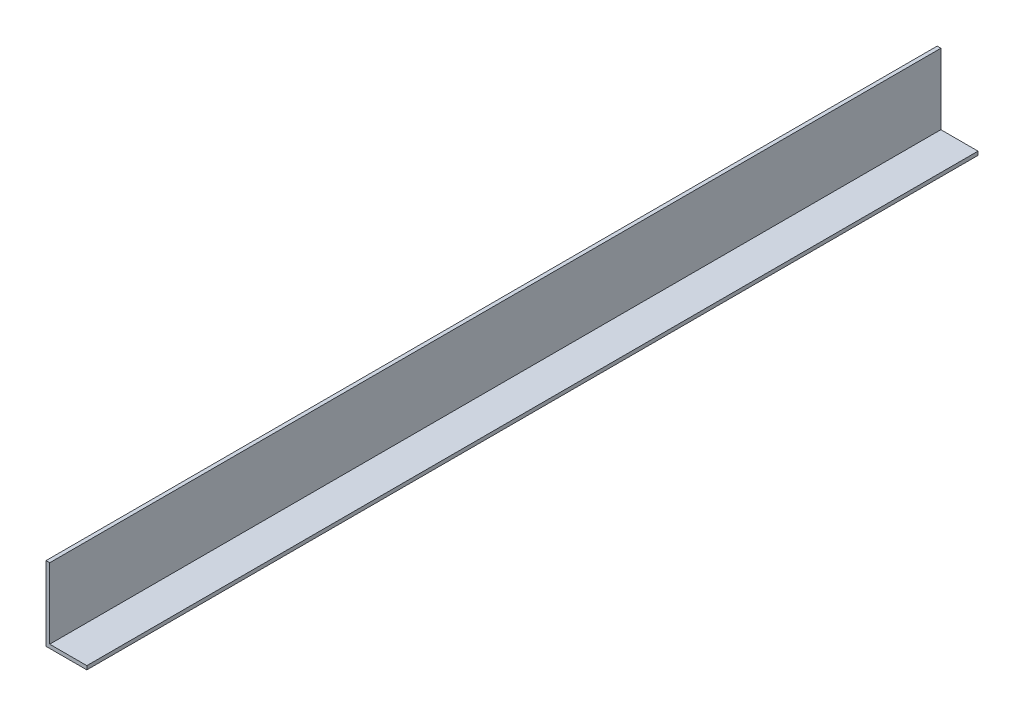
SolidWorks part; units mm, degrees
ref_plane "Plan de face" through (0, 0, 0) normal (0, 0, 1) x (1, 0, 0)
ref_plane "Plan de dessus" through (0, 0, 0) normal (0, 1, 0) x (1, 0, 0)
ref_plane "Plan de droite" through (0, 0, 0) normal (1, 0, 0) x (0, 0, -1)
sketch "Esquisse1" plane through (0, 0, 0) normal (0, 0, 1) x (1, 0, 0)
  line L0 (0, 0) -> (0, 20)
  line L1 (0, 20) -> (1, 20)
  line L2 (1, 20) -> (1, 1)
  line L3 (1, 1) -> (11, 1)
  line L4 (11, 1) -> (11, 0)
  line L5 (11, 0) -> (0, 0)
  dimension "D1" = 11
  dimension "D2" = 20
  dimension "D3" = 1
  dimension "D4" = 1
extrude "Boss.-Extru.1" add sketch "Esquisse1" along normal blind 240
sketch "Esquisse2" plane through (0, 0, 0) normal (-1, 0, 0) x (0, 0, 1)
  line L0 (120, 20) -> (120, 0) construction
  line L1 (240, 20) -> (0, 20) construction
  line L2 (240, 0) -> (0, 0) construction
  line L3 (120, 20) -> (115, 15)
  line L4 (115, 15) -> (110, 20)
  line L6 (110, 20) -> (105, 15)
  line L7 (105, 15) -> (100, 20)
  line L8 (100, 20) -> (95, 15)
  line L9 (95, 15) -> (90, 20)
  line L10 (90, 20) -> (85, 15)
  line L11 (85, 15) -> (80, 20)
  line L12 (80, 20) -> (75, 15)
  line L13 (75, 15) -> (70, 20)
  line L14 (70, 20) -> (65, 15)
  line L15 (65, 15) -> (60, 20)
  line L16 (60, 20) -> (55, 15)
  line L17 (55, 15) -> (50, 20)
  line L18 (50, 20) -> (45, 15)
  line L19 (45, 15) -> (40, 20)
  line L20 (40, 20) -> (35, 15)
  line L21 (35, 15) -> (30, 20)
  line L22 (30, 20) -> (25, 15)
  line L23 (25, 15) -> (20, 20)
  line L24 (20, 20) -> (15, 15)
  line L25 (15, 15) -> (10, 20)
  line L26 (10, 20) -> (5, 15)
  line L27 (5, 15) -> (0, 20)
  line L28 (235, 15) -> (240, 20)
  line L29 (230, 20) -> (235, 15)
  line L30 (225, 15) -> (230, 20)
  line L31 (220, 20) -> (225, 15)
  line L32 (215, 15) -> (220, 20)
  line L33 (210, 20) -> (215, 15)
  line L34 (205, 15) -> (210, 20)
  line L35 (200, 20) -> (205, 15)
  line L36 (195, 15) -> (200, 20)
  line L37 (190, 20) -> (195, 15)
  line L38 (185, 15) -> (190, 20)
  line L39 (180, 20) -> (185, 15)
  line L40 (175, 15) -> (180, 20)
  line L41 (170, 20) -> (175, 15)
  line L42 (165, 15) -> (170, 20)
  line L43 (160, 20) -> (165, 15)
  line L44 (155, 15) -> (160, 20)
  line L45 (150, 20) -> (155, 15)
  line L46 (145, 15) -> (150, 20)
  line L47 (140, 20) -> (145, 15)
  line L48 (135, 15) -> (140, 20)
  line L49 (130, 20) -> (135, 15)
  line L50 (125, 15) -> (130, 20)
  line L51 (120, 20) -> (125, 15)
  line L52 (0, 20) -> (0, 30)
  line L53 (0, 30) -> (240, 30)
  line L54 (240, 30) -> (240, 20)
  dimension "D1" = 10
  dimension "D3" = 10
  dimension "D2" = 12
extrude "Enlèv. mat.-Extru.1" [suppressed] cut sketch "Esquisse2" against normal through all both and the other way through all
